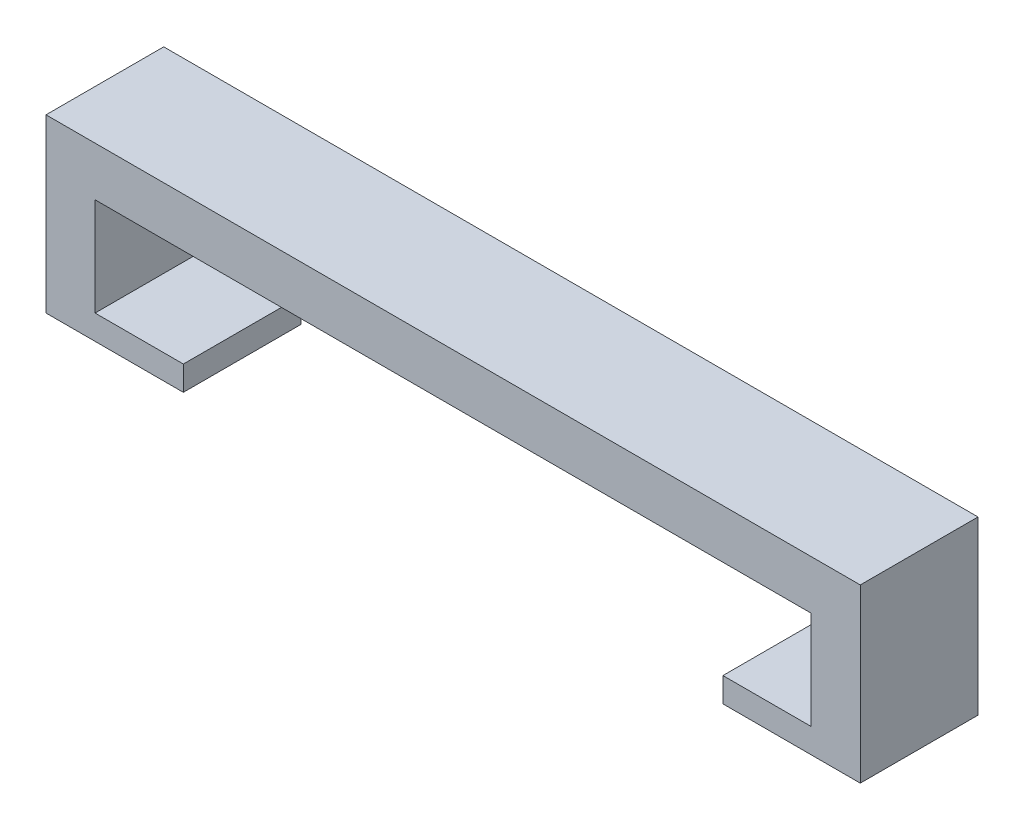
SolidWorks part; units mm, degrees
ref_plane "Ön Düzlem" through (0, 0, 0) normal (0, 0, 1) x (1, 0, 0)
ref_plane "Üst Düzlem" through (0, 0, 0) normal (0, 1, 0) x (1, 0, 0)
ref_plane "Sağ Düzlem" through (0, 0, 0) normal (1, 0, 0) x (0, 0, -1)
sketch "Çizim1" plane through (0, 0, 0) normal (0, 0, 1) x (1, 0, 0)
  line L0 (4.2052, -0.8057) -> (4.2052, -0.3057)
  line L1 (-9.5948, 2.6943) -> (7.0052, 2.6943)
  line L2 (-9.5948, 2.6943) -> (-9.5948, -0.8057)
  line L3 (-9.5948, -0.8057) -> (-6.7948, -0.8057)
  line L4 (7.0052, 2.6943) -> (7.0052, -0.8057)
  line L7 (4.2052, -0.3057) -> (6.0052, -0.3057)
  line L8 (6.0052, -0.3057) -> (6.0052, 1.6943)
  line L9 (6.0052, 1.6943) -> (-8.5948, 1.6943)
  line L10 (-8.5948, 1.6943) -> (-8.5948, -0.3057)
  line L11 (-8.5948, -0.3057) -> (-6.7948, -0.3057)
  line L12 (-6.7948, -0.3057) -> (-6.7948, -0.8057)
  line L13 (4.2052, -0.8057) -> (7.0052, -0.8057)
  point P0 (0, 0)
  dimension "D1" = 1
  dimension "D2" = 2
  dimension "D3" = 1.8
  dimension "D4" = 1
  dimension "D5" = 11
  dimension "D6" = 1
  dimension "D7" = 0.5
extrude "Yükseklik-Ekstrüzyon1" add sketch "Çizim1" along normal blind 2.4
